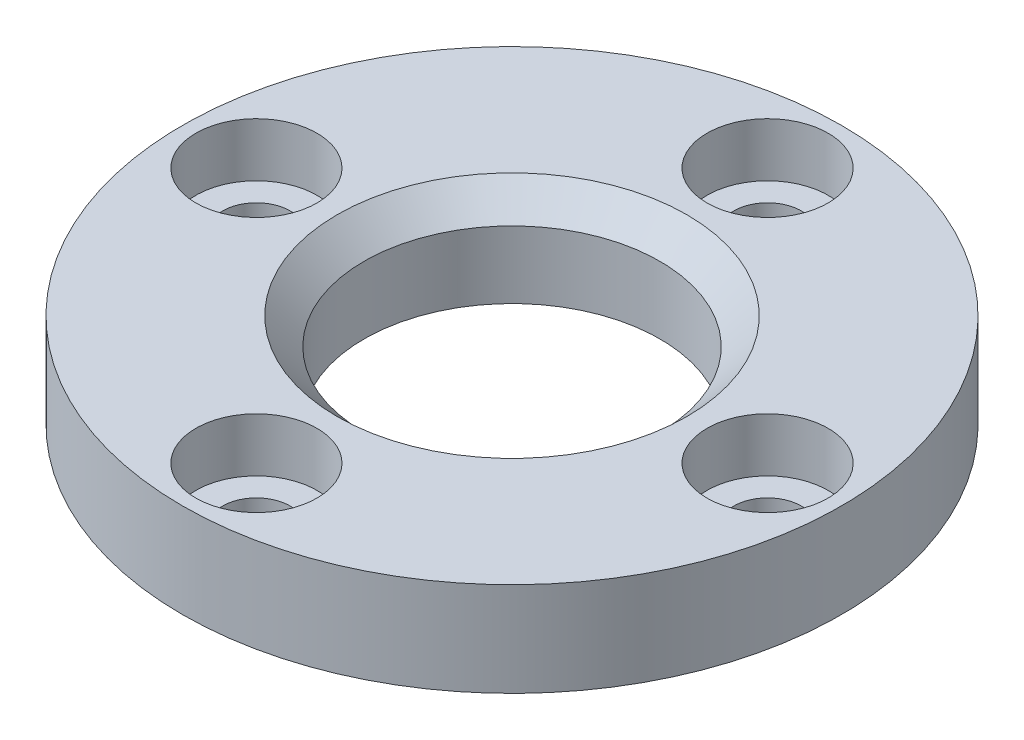
SolidWorks part; units mm, degrees
ref_plane "Спереди" through (0, 0, 0) normal (0, 0, 1) x (1, 0, 0)
ref_plane "Сверху" through (0, 0, 0) normal (0, 1, 0) x (1, 0, 0)
ref_plane "Справа" through (0, 0, 0) normal (1, 0, 0) x (0, 0, -1)
sketch "Эскиз1" plane through (0, 0, 0) normal (0, 1, 0) x (1, 0, 0)
  circle A0 centre (0, 0) radius 12.25
  circle A1 centre (0, 0) radius 5.5
  circle A2 centre (0, 0) radius 9.5 construction
  circle A3 centre (0, 9.5) radius 1.25
  circle A4 centre (9.5, 0) radius 1.25
  circle A5 centre (0, -9.5) radius 1.25
  circle A6 centre (-9.5, 0) radius 1.25
  point P7 (0, 0)
  point P8 (0, 0)
  dimension "D1" = 24.5
  dimension "D2" = 11
  dimension "D3" = 19
  dimension "D4" = 2.5
  dimension "D5" = 4
extrude "Бобышка-Вытянуть1" add sketch "Эскиз1" along normal blind 3.5
sketch "Эскиз2" plane through (0, 3.5, 0) normal (0, 1, 0) x (1, 0, 0)
  circle A0 centre (0, 9.5) radius 2.25
  circle A2 centre (9.5, 0) radius 2.25
  circle A3 centre (0, -9.5) radius 2.25
  circle A4 centre (-9.5, 0) radius 2.25
  circle A5 centre (9.5, 0) radius 1.25 construction
  dimension "D1" = 4.5
  dimension "D2" = 4
extrude "Вырез-Вытянуть1" cut sketch "Эскиз2" against normal blind 2
chamfer "Фаска1" distance 1 angle 45 1 edges at (0, 3.5, 5.5)
